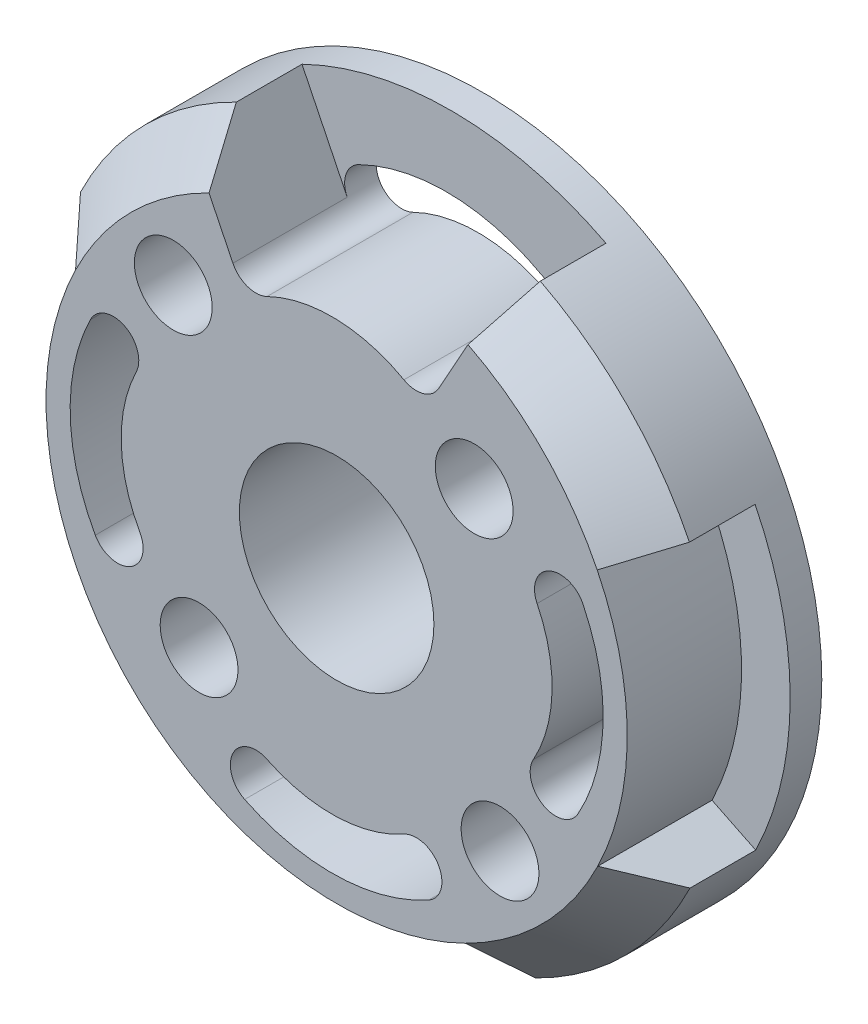
SolidWorks part; units mm, degrees
ref_plane "Ön Düzlem" through (0, 0, 0) normal (0, 0, 1) x (1, 0, 0)
ref_plane "Üst Düzlem" through (0, 0, 0) normal (0, 1, 0) x (1, 0, 0)
ref_plane "Sağ Düzlem" through (0, 0, 0) normal (1, 0, 0) x (0, 0, -1)
sketch "Çizim1" plane through (0, 0, 0) normal (0, 0, 1) x (1, 0, 0)
  circle A0 centre (0, 0) radius 13.95
  circle A1 centre (0, 0) radius 4
  dimension "D1" = 27.9
  dimension "D2" = 8
extrude "Yükseklik-Ekstrüzyon3" add sketch "Çizim1" along normal blind 6
sketch "Çizim4" plane through (0, 0, 0) normal (0, 0, 1) x (1, 0, 0)
  line L0 (0, 0) -> (-9.8641, 9.8641) construction
  line L1 (0, 0) -> (-13.95, 0) construction
  line L2 (0, 0) -> (-9.8641, -9.8641) construction
  line L3 (0, 0) -> (0, -13.95) construction
  circle A0 centre (0, 0) radius 13.95 construction
  point P1 (-5.6569, -5.6569)
  point P2 (6.7175, -6.7175)
  point P6 (5.6569, 5.6569)
  point P9 (-6.7175, 6.7175)
  dimension "D1" = 9.5
  dimension "D2" = 8
  dimension "D3" = 45
  dimension "D5" = 45
sketch "Çizim7" plane through (0, 0, 6) normal (0, 0, 1) x (1, 0, 0)
sketch "Çizim10" plane through (0, 0, 0) normal (0, 0, -1) x (-1, 0, 0)
hole_wizard "M3 Boşluklu Delik3" positions "Çizim11" profile "Çizim12" hole size "M3" standard "ANSI Metrik" end condition through all
sketch "Çizim11" plane through (0, 0, 0) normal (0, 0, -1) x (-1, 0, 0)
  point P0 (-5.6569, 5.6569)
  point P3 (-6.7175, -6.7175)
  point P6 (5.6569, -5.6569)
  point P9 (6.7175, 6.7175)
sketch "Çizim12" plane through (5.6569, 5.6569, 0) normal (1, 0, 0) x (0, 1, 0)
  line L0 (0, 0) -> (0, 6)
  line L1 (0, 6) -> (1.6, 6)
  line L2 (1.6, 6) -> (1.6, 0)
  line L5 (1.6, 0) -> (0, 0)
  line L11 (0, -6.35) -> (0, 107.95) construction
  dimension "Thru Hole Dia." = 3.2
  dimension "Thru Hole Depth" = 6
sketch "Çizim13" plane through (0, 0, 6) normal (0, 0, 1) x (1, 0, 0)
  line L1 (0, 0) -> (-13.95, 0) construction
  line L2 (0, 0) -> (0, -15.6098) construction
  arc A0 (9.0078, -3.2781) -> (9.186, 3.3219) centre (2.779, 0.1924) ccw construction
  arc A1 (-9.0078, -3.2781) -> (-9.186, 3.3219) centre (-2.779, 0.1924) cw construction
  arc A2 (-10.1295, 3.7827) -> (-9.9251, -3.7892) centre (-2.779, 0.1924) ccw
  arc A3 (-8.2425, 2.861) -> (-8.0906, -2.7671) centre (-2.779, 0.1924) ccw
  arc A4 (-8.2425, 2.861) -> (-10.1295, 3.7827) centre (-9.186, 3.3219) ccw
  arc A5 (-9.9251, -3.7892) -> (-8.0906, -2.7671) centre (-9.0078, -3.2781) ccw
  arc A7 (10.1295, 3.7827) -> (9.9251, -3.7892) centre (2.779, 0.1924) cw
  arc A8 (8.2425, 2.861) -> (8.0906, -2.7671) centre (2.779, 0.1924) cw
  arc A9 (8.2425, 2.861) -> (10.1295, 3.7827) centre (9.186, 3.3219) cw
  arc A10 (9.9251, -3.7892) -> (8.0906, -2.7671) centre (9.0078, -3.2781) cw
  point P1 (-10.9256, 0)
  point P3 (-9.9068, 0)
  point P5 (-13.95, 0)
  point P18 (9.9068, 0)
  point P23 (10.9256, 0)
  dimension "D1" = 2.1
  dimension "D2" = 6.6
  dimension "D3" = 3.0244
extrude "Kes-Ekstrüzyon2" cut sketch "Çizim13" against normal blind 6
pattern_circular "Dairesel Kaplama1" count 2 every 90 about axis through (0, 0, 0) along (0, 0, 1) of "Kes-Ekstrüzyon2"
sketch "Çizim16" plane through (0, 0, 6) normal (0, 0, 1) x (1, 0, 0)
  line L0 (-4.2653, 8.7252) -> (-6.8586, 14.0345)
  line L1 (4.1954, 8.4968) -> (8.9438, 17.0191)
  line L2 (8.9438, 17.0191) -> (-6.8586, 14.0345)
  arc A0 (-3.7827, 10.1295) -> (-2.861, 8.2425) centre (-3.3219, 9.186) ccw construction
  circle A1 centre (0, 0) radius 13.95
  circle A2 centre (0, 0) radius 13.95
  arc A3 (3.7892, 9.9251) -> (-3.7827, 10.1295) centre (-0.1924, 2.779) ccw construction
  arc A4 (2.7671, 8.0906) -> (3.7892, 9.9251) centre (3.2781, 9.0078) ccw construction
  arc A5 (2.7671, 8.0906) -> (3.7892, 9.9251) centre (3.2781, 9.0078) ccw
  arc A6 (3.7892, 9.9251) -> (-3.7827, 10.1295) centre (-0.1924, 2.779) ccw
  arc A7 (-3.7827, 10.1295) -> (-2.861, 8.2425) centre (-3.3219, 9.186) ccw
  arc M2 (-2.861, 8.2425) -> (-3.7827, 10.1295) centre (-3.3219, 9.186) cw
  arc M3 (-3.7827, 10.1295) -> (3.7892, 9.9251) centre (-0.1924, 2.779) cw
  arc M4 (3.7892, 9.9251) -> (2.7671, 8.0906) centre (3.2781, 9.0078) cw
  circle M14 centre (0, 0) radius 13.95
  dimension "D1" = 0
extrude "Kes-Ekstrüzyon11" cut sketch "Çizim16" against normal blind 4.7 contours L1 L0 M4 M14 M2 M3
chamfer "Pah1" distance 2 angle 45 1 edges at (-0.1395, -13.9493, 6)
sketch "Çizim18" plane through (0, 0, 6) normal (0, 0, 1) x (1, 0, 0)
  line L0 (-10.7358, 5.2483) -> (-12.5326, 6.1266)
  line L1 (-10.7143, -5.2921) -> (-12.5075, -6.1778)
  arc A0 (-8.2425, 2.861) -> (-10.1295, 3.7827) centre (-9.186, 3.3219) ccw construction
  arc A1 (-9.9251, -3.7892) -> (-8.0906, -2.7671) centre (-9.0078, -3.2781) ccw construction
  arc A2 (-5.2476, 10.7362) -> (5.4007, 10.66) centre (0, 0) ccw construction
  arc A3 (-10.7358, 5.2483) -> (-10.7143, -5.2921) centre (0, 0) ccw
  arc A4 (-6.1254, 12.5333) -> (6.3748, 12.4083) centre (0, 0) ccw construction
  arc A5 (-12.5326, 6.1266) -> (-12.5075, -6.1778) centre (0, 0) ccw
extrude "Kes-Ekstrüzyon12" cut sketch "Çizim18" against normal blind 4.7
pattern_circular "Dairesel Kaplama2" count 3 every 90 about axis through (0, 0, 6) along (0, 0, 1) of "Kes-Ekstrüzyon12"
